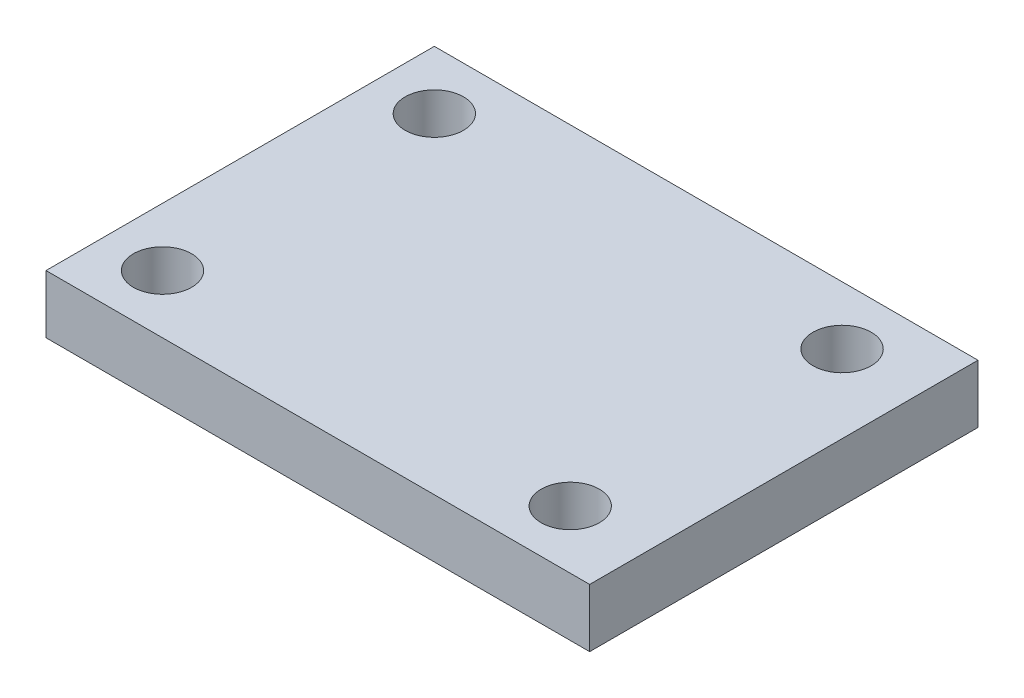
SolidWorks part; units mm, degrees
ref_plane "Front Plane" through (0, 0, 0) normal (0, 0, 1) x (1, 0, 0)
ref_plane "Top Plane" through (0, 0, 0) normal (0, 1, 0) x (1, 0, 0)
ref_plane "Right Plane" through (0, 0, 0) normal (1, 0, 0) x (0, 0, -1)
sketch "Sketch1" plane through (0, 0, 0) normal (0, 1, 0) x (1, 0, 0)
  line L1 (-14, 10) -> (14, 10)
  line L2 (-14, 10) -> (-14, -10)
  line L3 (-14, -10) -> (14, -10)
  line L4 (14, 10) -> (14, -10)
  line L5 (-14, 10) -> (14, -10) construction
  line L6 (-14, -10) -> (14, 10) construction
  circle A0 centre (-11, 7) radius 1.5
  circle A1 centre (10, 7) radius 1.5
  circle A2 centre (-11, -7) radius 1.5
  circle A3 centre (10, -7) radius 1.5
  point P0 (0, 0)
  point P14 (0, 0)
  point P15 (0, 0)
  point P16 (0, 0)
  point P17 (0, 0)
  point P18 (0, 0)
  point P19 (0, 0)
  dimension "D9" = 3
  dimension "D10" = 3
  dimension "D11" = 3
  dimension "D12" = 3
  dimension "D1" = 28
  dimension "D2" = 20
  dimension "D3" = 21
  dimension "D4" = 21
  dimension "D5" = 3
  dimension "D6" = 14
  dimension "D7" = 14
  dimension "D8" = 3
extrude "Boss-Extrude1" add sketch "Sketch1" along normal blind 3 contours L4 L1 L2 L3 A3 A2 A1 A0
